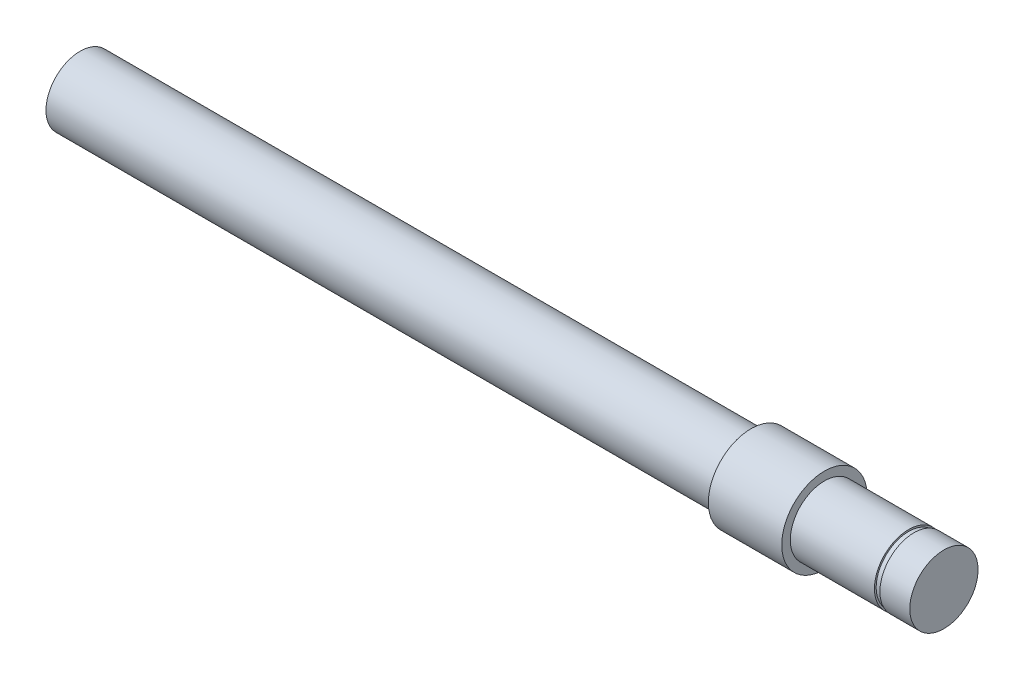
SolidWorks part; units mm, degrees
material "5052-H32"
ref_plane "Front Plane" through (0, 0, 0) normal (0, 0, 1) x (1, 0, 0)
ref_plane "Top Plane" through (0, 0, 0) normal (0, 1, 0) x (1, 0, 0)
ref_plane "Right Plane" through (0, 0, 0) normal (1, 0, 0) x (0, 0, -1)
sketch "Sketch1" plane through (0, 0, 0) normal (0, 0, 1) x (1, 0, 0)
  line L0 (0, 2) -> (0, 0)
  line L1 (0, 0) -> (38.6, 0)
  line L2 (38.6, 3) -> (38.6, -3) construction
  line L3 (38.6, 0) -> (38.6, 2)
  line L4 (38.6, 2) -> (36.85, 2)
  line L5 (36.85, 2) -> (36.85, 1.9)
  line L6 (36.85, 1.9) -> (36.53, 1.9)
  line L7 (36.53, 1.9) -> (36.53, 2)
  line L8 (36.53, 2) -> (31.6, 2)
  line L9 (31.6, 2) -> (31.6, 2.5)
  line L10 (31.6, 2.5) -> (27.3, 2.5)
  line L11 (27.3, 2.5) -> (27.3, 2)
  line L12 (27.3, 5.25) -> (27.3, -5.25) construction
  line L13 (0, 2) -> (38.6, 2) construction
  line L14 (27.3, 2) -> (0, 2)
  line L15 (36.6, 2) -> (36.6, 1.9) construction
  line L16 (0, 0) -> (-12, 0)
  line L17 (-12, 0) -> (-12, 2)
  line L18 (-12, 2) -> (0, 2)
revolve "Revolve1" add sketch "Sketch1" angle 360 about L1
